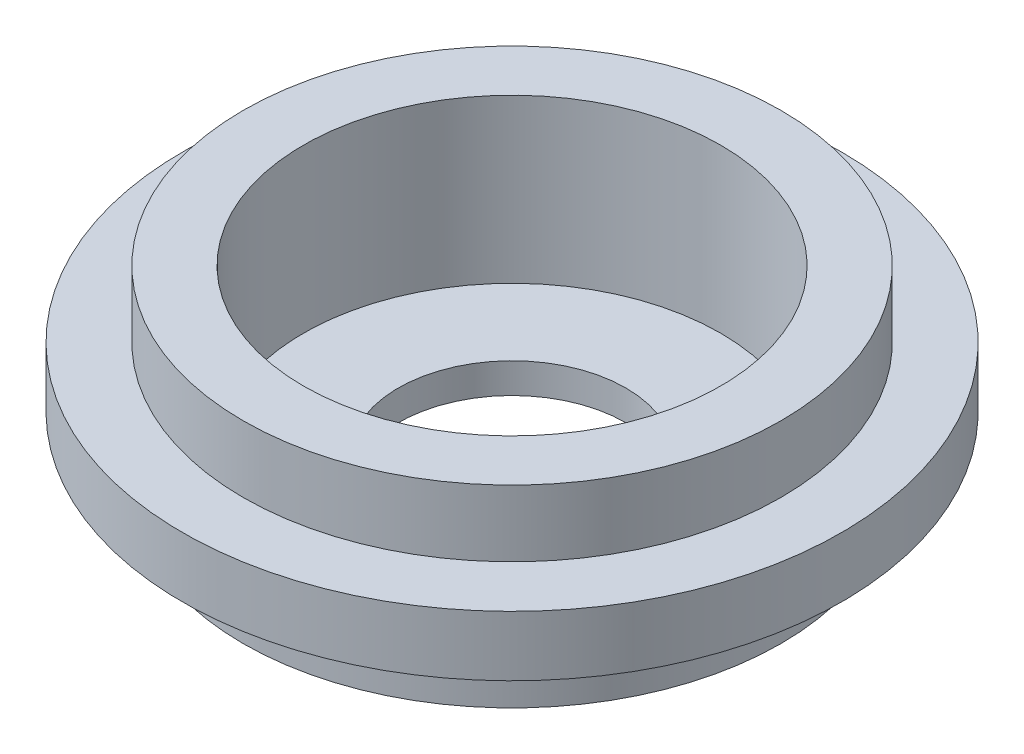
SolidWorks part; units mm, degrees
ref_plane "Top Plane" through (0, 0, 0) normal (0, 0, 1) x (1, 0, 0)
ref_plane "Front Plane" through (0, 0, 0) normal (0, 1, 0) x (1, 0, 0)
ref_plane "Right Plane" through (0, 0, 0) normal (1, 0, 0) x (0, 0, -1)
sketch "Profile Sketch" plane through (0, 0, 0) normal (1, 0, 0) x (0, 0, -1)
  line L0 (-6, -3.5) -> (-6, -5.0875)
  line L1 (-14.175, 1.585) -> (-14.175, 5.0875)
  line L2 (-11, -5.0875) -> (-14.175, -5.0875)
  line L3 (-11, -3.5) -> (-11, 5.0875)
  line L4 (-11, 5.0875) -> (-14.175, 5.0875)
  line L5 (-14.175, -5.0875) -> (-14.175, -1.585)
  line L6 (-11, -5.0875) -> (-14.175, 5.0875) construction
  line L7 (-11, 5.0875) -> (-14.175, -5.0875) construction
  line L8 (-17.375, -1.585) -> (-14.175, -1.585)
  line L9 (-17.375, -1.585) -> (-17.375, 1.585)
  line L10 (-17.375, 1.585) -> (-14.175, 1.585)
  line L11 (0, -5.0875) -> (0, 5.0875) construction
  line L12 (-17.375, -1.585) -> (-14.175, 1.585) construction
  line L13 (-17.375, 1.585) -> (-14.175, -1.585) construction
  line L14 (-11, -5.0875) -> (-6, -5.0875)
  line L15 (-11, -3.5) -> (-6, -3.5)
  point P3 (-12.5875, 0)
  point P8 (-15.775, 0)
  dimension "D1" = 11
  dimension "D2" = 3.175
  dimension "D3" = 3.17
  dimension "D4" = 3.2
  dimension "D5" = 1.5875
  dimension "D6" = 8.5875
  dimension "D7" = 6
revolve "Profile Revolve" add sketch "Profile Sketch" angle 360 about L11
